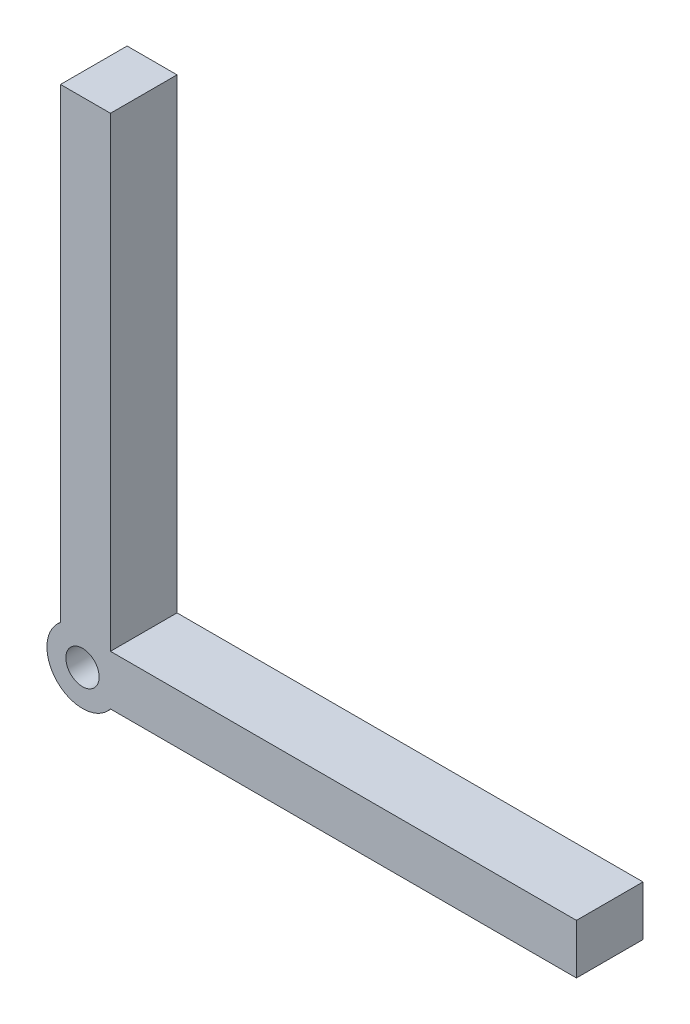
SolidWorks part; units mm, degrees
ref_plane "Front Plane" through (0, 0, 0) normal (0, 0, 1) x (1, 0, 0)
ref_plane "Top Plane" through (0, 0, 0) normal (0, 1, 0) x (1, 0, 0)
ref_plane "Right Plane" through (0, 0, 0) normal (1, 0, 0) x (0, 0, -1)
sketch "Sketch1" plane through (0, 0, 0) normal (0, 0, 1) x (1, 0, 0)
  line L0 (-12.7709, -21.3494) -> (-12.7709, 48.6506)
  line L17 (-12.7709, 48.6506) -> (-5.2709, 48.6506)
  line L18 (-5.2709, 48.6506) -> (-5.2709, -21.3494)
  line L19 (-5.2709, -21.3494) -> (64.7291, -21.3494)
  line L20 (64.7291, -21.3494) -> (64.7291, -28.8494)
  line L21 (64.7291, -28.8494) -> (-5.2709, -28.8494)
  circle A1 centre (-9.4734, -25.5519) radius 5.3418
  point P4 (-5.6746, -29.3074)
  dimension "D5" = 70
  dimension "D1" = 70
  dimension "D2" = 70
  dimension "D3" = 7.5
  dimension "D4" = 70
  dimension "D6" = 7.5
extrude "Boss-Extrude2" add sketch "Sketch1" along normal blind 10 contours A1 L21 L20 L19 L18 L17 L0 | A1 L20
sketch "Sketch2" plane through (0, 0, 0) normal (0, 0, -1) x (-1, 0, 0)
  circle A0 centre (9.4734, -25.5519) radius 2.5
extrude "Cut-Extrude1" cut sketch "Sketch2" against normal blind 10
